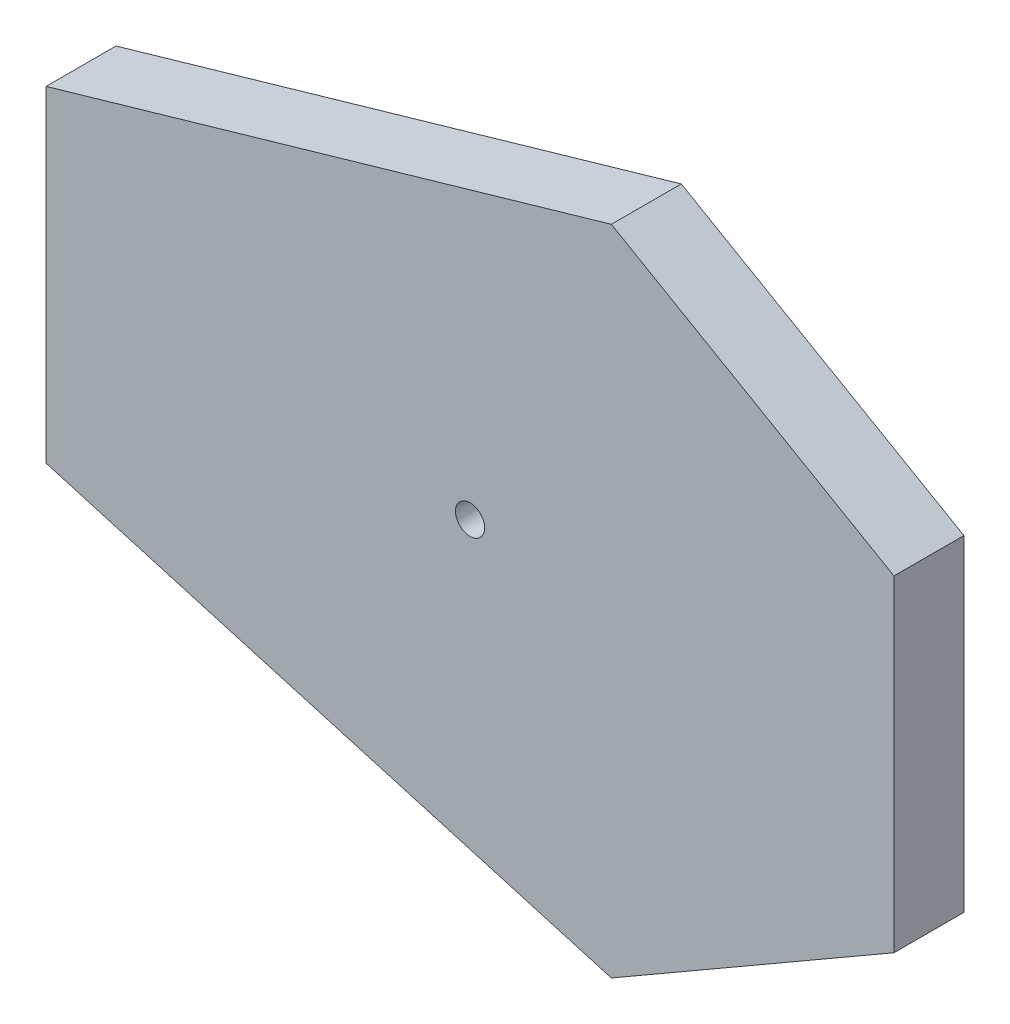
SolidWorks part; units mm, degrees
ref_plane "Front Plane" through (0, 0, 0) normal (0, 0, 1) x (1, 0, 0)
ref_plane "Top Plane" through (0, 0, 0) normal (0, 1, 0) x (1, 0, 0)
ref_plane "Right Plane" through (0, 0, 0) normal (1, 0, 0) x (0, 0, -1)
sketch "Sketch1" plane through (0, 0, 0) normal (0, 0, 1) x (1, 0, 0)
  line L0 (-41.5231, 14) -> (-41.5231, -14) construction
  line L1 (6.9744, -28) -> (-41.5231, -14) construction
  line L2 (6.9744, -28) -> (31.2231, -14) construction
  line L3 (31.2231, -14) -> (31.2231, 14) construction
  line L4 (31.2231, 14) -> (6.9744, 28) construction
  line L5 (-41.5231, 14) -> (6.9744, 28) construction
  line L6 (-41.5231, 14) -> (-41.5231, -14)
  line L7 (6.9744, -28) -> (-41.5231, -14)
  line L8 (6.9744, -28) -> (31.2231, -14)
  line L9 (31.2231, -14) -> (31.2231, 14)
  line L10 (31.2231, 14) -> (6.9744, 28)
  line L11 (-41.5231, 14) -> (6.9744, 28)
  circle A0 centre (-5.15, 0) radius 1.25
  dimension "D1" = 2.5
extrude "Boss-Extrude1" add sketch "Sketch1" along normal blind 6
sketch "Sketch2" plane through (0, 0, 0) normal (0, 0, -1) x (-1, 0, 0)
  arc A1 (5.8221, -1.9895) -> (5.8221, 1.9895) centre (5.15, 0) ccw construction
  circle A2 centre (5.15, 0) radius 2.1
extrude "Cut-Extrude1" cut sketch "Sketch2" against normal blind 3
